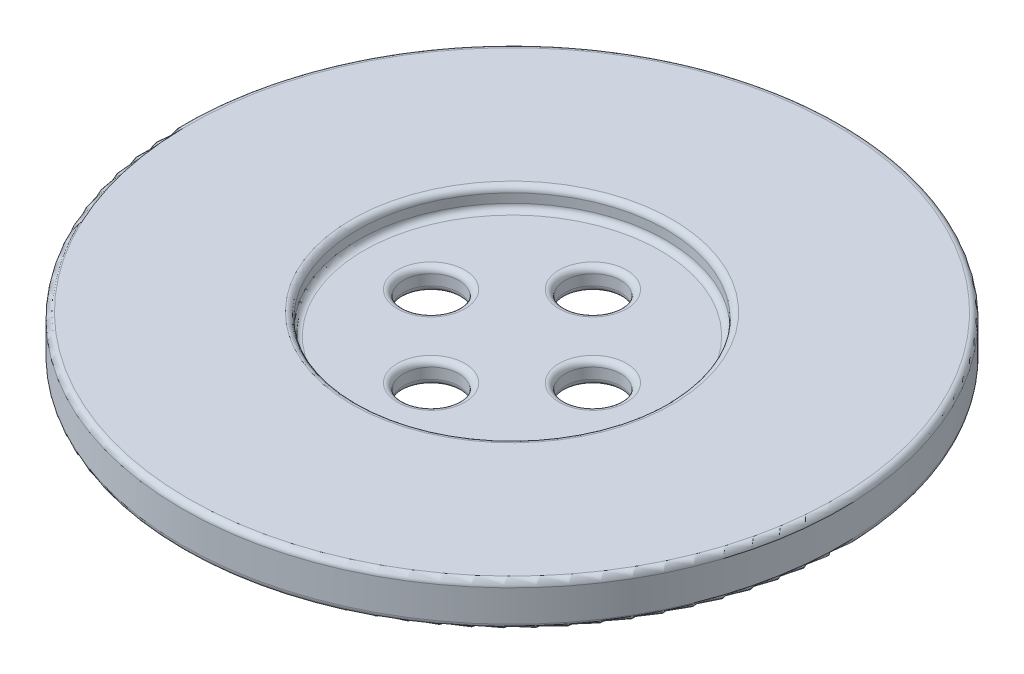
SolidWorks part; units mm, degrees
ref_plane "Front Plane" through (0, 0, 0) normal (0, 0, 1) x (1, 0, 0)
ref_plane "Top Plane" through (0, 0, 0) normal (0, 1, 0) x (1, 0, 0)
ref_plane "Right Plane" through (0, 0, 0) normal (1, 0, 0) x (0, 0, -1)
sketch "Sketch1" plane through (0, 0, 0) normal (0, 1, 0) x (1, 0, 0)
  line L0 (0, 5.4) -> (0, 0) construction
  circle A0 centre (0, 0) radius 22
  circle A1 centre (0, 5.4) radius 1.85
  circle A2 centre (5.4, 0) radius 1.85
  circle A3 centre (0, -5.4) radius 1.85
  circle A4 centre (-5.4, 0) radius 1.85
  point P5 (8.6046, 1.7046)
  point P6 (0, 0)
  point P14 (0, 0)
  dimension "D1" = 5.4
  dimension "D2" = 3.7
  dimension "D3" = 44
  dimension "D4" = 4
extrude "Boss-Extrude1" add sketch "Sketch1" along normal blind 2.9
sketch "Sketch2" plane through (0, 2.9, 0) normal (0, 1, 0) x (1, 0, 0)
  circle A0 centre (0, 0) radius 10.3
  dimension "D1" = 20.6
extrude "Cut-Extrude1" cut sketch "Sketch2" against normal blind 1.4
fillet "Fillet1" radius 0.4 12 edges at (0, 0, 22) (0, 2.9, 22) (0, 2.9, 10.3) (0, 1.5, 10.3) (0, 1.5, 7.25) (0, 0, 7.25) (5.4, 1.5, 1.85) (5.4, 0, 1.85) (0, 1.5, -3.55) (0, 0, -3.55) (-5.4, 1.5, 1.85) (-5.4, 0, 1.85)
